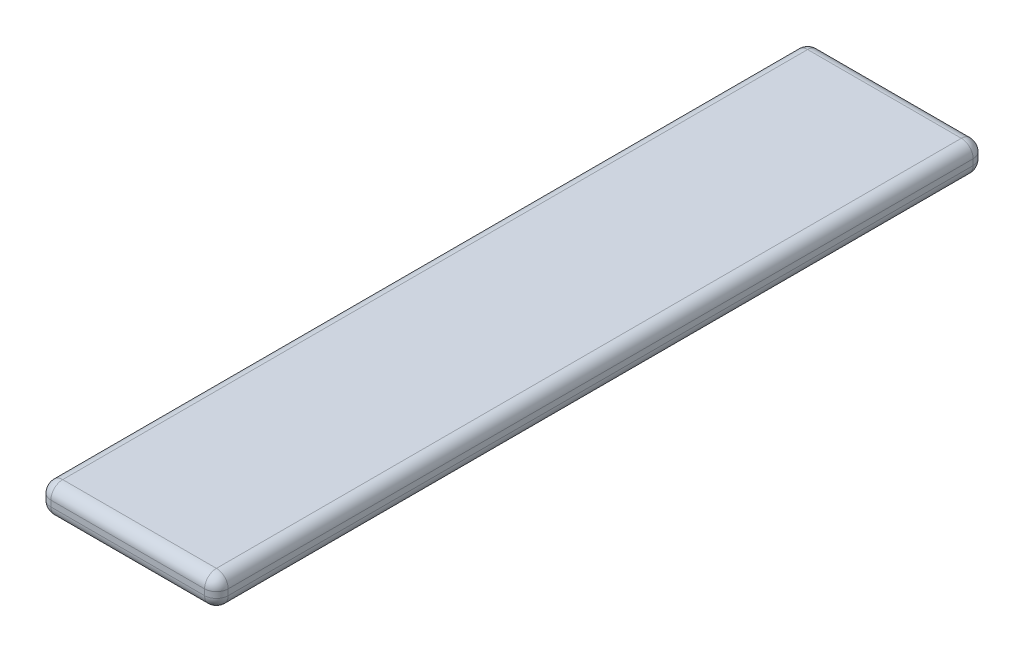
SolidWorks part; units mm, degrees
material "Balsa"
ref_plane "Front Plane" through (0, 0, 0) normal (0, 0, 1) x (1, 0, 0)
ref_plane "Top Plane" through (0, 0, 0) normal (0, 1, 0) x (1, 0, 0)
ref_plane "Right Plane" through (0, 0, 0) normal (1, 0, 0) x (0, 0, -1)
sketch "Sketch1" plane through (0, 0, 0) normal (0, 1, 0) x (1, 0, 0)
  line L1 (0, 0) -> (38.1, 0)
  line L2 (0, 0) -> (0, 165.1)
  line L3 (0, 165.1) -> (38.1, 165.1)
  line L4 (38.1, 0) -> (38.1, 165.1)
  dimension "D1" = 38.1
  dimension "D2" = 165.1
extrude "Boss-Extrude1" add sketch "Sketch1" along normal blind 6.35 contours L2 L1 L4 L3
fillet "Fillet1" radius 2.54 12 edges at (0, 3.175, 0) (38.1, 3.175, 0) (19.05, 0, -165.1) (19.05, 6.35, -165.1) (19.05, 6.35, 0) (0, 3.175, -165.1) (38.1, 3.175, -165.1) (38.1, 6.35, -82.55) (38.1, 0, -82.55) (19.05, 0, 0) (0, 0, -82.55) (0, 6.35, -82.55)
